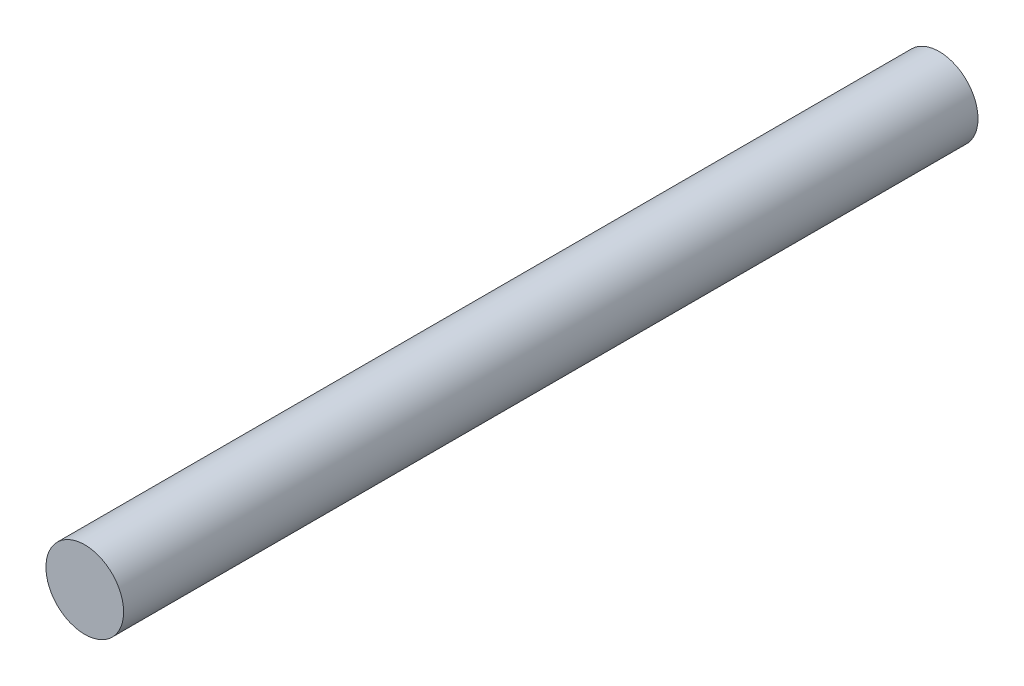
SolidWorks part; units mm, degrees
material "AISI 1020 Steel, Cold Rolled"
ref_plane "Front Plane" through (0, 0, 0) normal (0, 0, 1) x (1, 0, 0)
ref_plane "Top Plane" through (0, 0, 0) normal (0, 1, 0) x (1, 0, 0)
ref_plane "Right Plane" through (0, 0, 0) normal (1, 0, 0) x (0, 0, -1)
sketch "Sketch1" plane through (0, 0, 0) normal (0, 0, 1) x (1, 0, 0)
  circle A0 centre (0, 0) radius 2.5
  dimension "D1" = 5
extrude "Boss-Extrude1" add sketch "Sketch1" along normal blind 55
sketch "Sketch2" [suppressed] plane through (0, 0, 0) normal (0, 0, -1) x (-1, 0, 0)
  circle A0 centre (0, 0) radius 2.5
  circle A1 centre (0, 0) radius 2.5 construction
extrude "Cut-Extrude1" [suppressed] cut sketch "Sketch2" against normal blind 35
sketch "Sketch3" [suppressed] plane through (0, 0, 0) normal (0, 0, -1) x (-1, 0, 0)
  circle A0 centre (0, 0) radius 2.5
  circle A1 centre (0, 0) radius 2.5 construction
